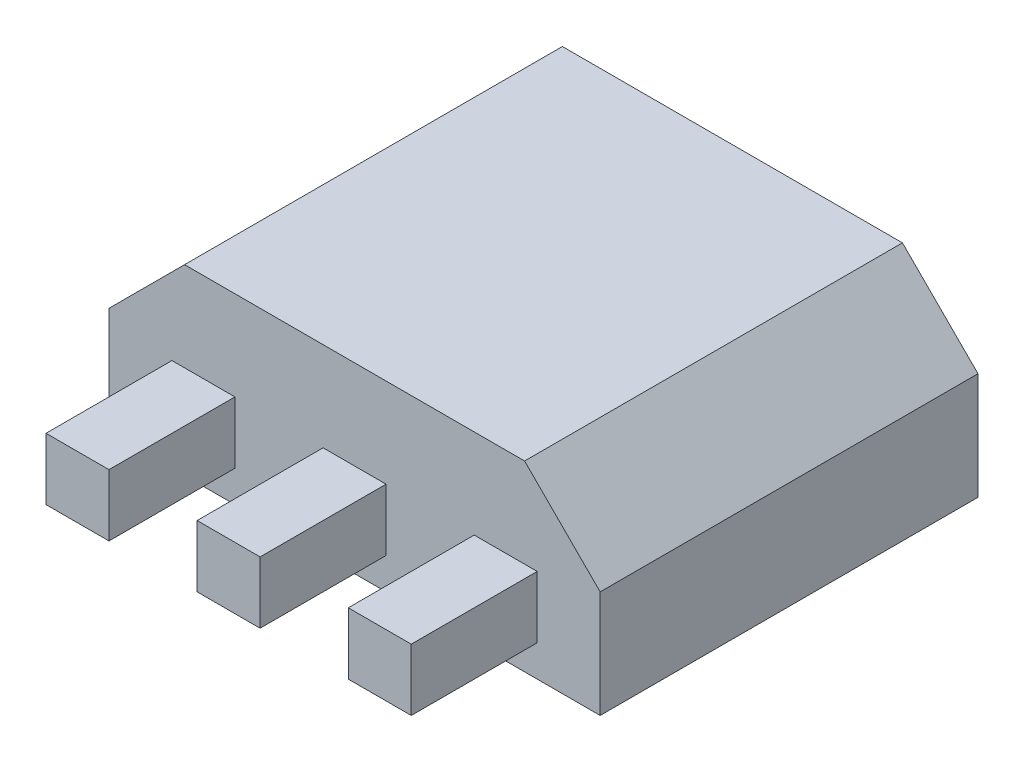
SolidWorks part; units mm, degrees
ref_plane "Front Plane" through (0, 0, 0) normal (0, 0, 1) x (1, 0, 0)
ref_plane "Top Plane" through (0, 0, 0) normal (0, 1, 0) x (1, 0, 0)
ref_plane "Right Plane" through (0, 0, 0) normal (1, 0, 0) x (0, 0, -1)
sketch "Sketch1" plane through (0, 0, 0) normal (0, 1, 0) x (1, 0, 0)
  line L1 (0, 0) -> (3.9, 0)
  line L2 (0, 0) -> (0, 3)
  line L3 (0, 3) -> (3.9, 3)
  line L4 (3.9, 0) -> (3.9, 3)
  dimension "D1" = 3.9
  dimension "D2" = 3
extrude "Boss-Extrude1" add sketch "Sketch1" along normal blind 1.45
chamfer "Chamfer1" distance 0.6 angle 45 2 edges at (0, 1.45, -1.5) (3.9, 1.45, -1.5)
sketch "Sketch2" plane through (0, 0, 0) normal (0, 0, 1) x (1, 0, 0)
  line L0 (0, 0) -> (3.9, 0) construction
  line L1 (0.5, 0.7406) -> (1, 0.7406)
  line L2 (0.5, 0.7406) -> (0.5, 0.25)
  line L3 (0.5, 0.25) -> (1, 0.25)
  line L4 (1, 0.7406) -> (1, 0.25)
  line L5 (1.7, 0.7406) -> (2.2, 0.7406)
  line L6 (1.7, 0.7406) -> (1.7, 0.25)
  line L7 (1.7, 0.25) -> (2.2, 0.25)
  line L8 (2.2, 0.7406) -> (2.2, 0.25)
  line L9 (2.9, 0.7406) -> (3.4, 0.7406)
  line L10 (2.9, 0.7406) -> (2.9, 0.25)
  line L11 (2.9, 0.25) -> (3.4, 0.25)
  line L12 (3.4, 0.7406) -> (3.4, 0.25)
  line L13 (0, 0.85) -> (0, 0) construction
  line L14 (3.9, 0.85) -> (3.9, 0) construction
  dimension "D1" = 0.5
  dimension "D2" = 0.5
  dimension "D3" = 0.5
  dimension "D4" = 0.25
  dimension "D5" = 0.25
  dimension "D6" = 0.25
  dimension "D7" = 0.5
  dimension "D8" = 0.5
  dimension "D9" = 0.7
  dimension "D10" = 0.7
extrude "Boss-Extrude2" add sketch "Sketch2" along normal blind 1
